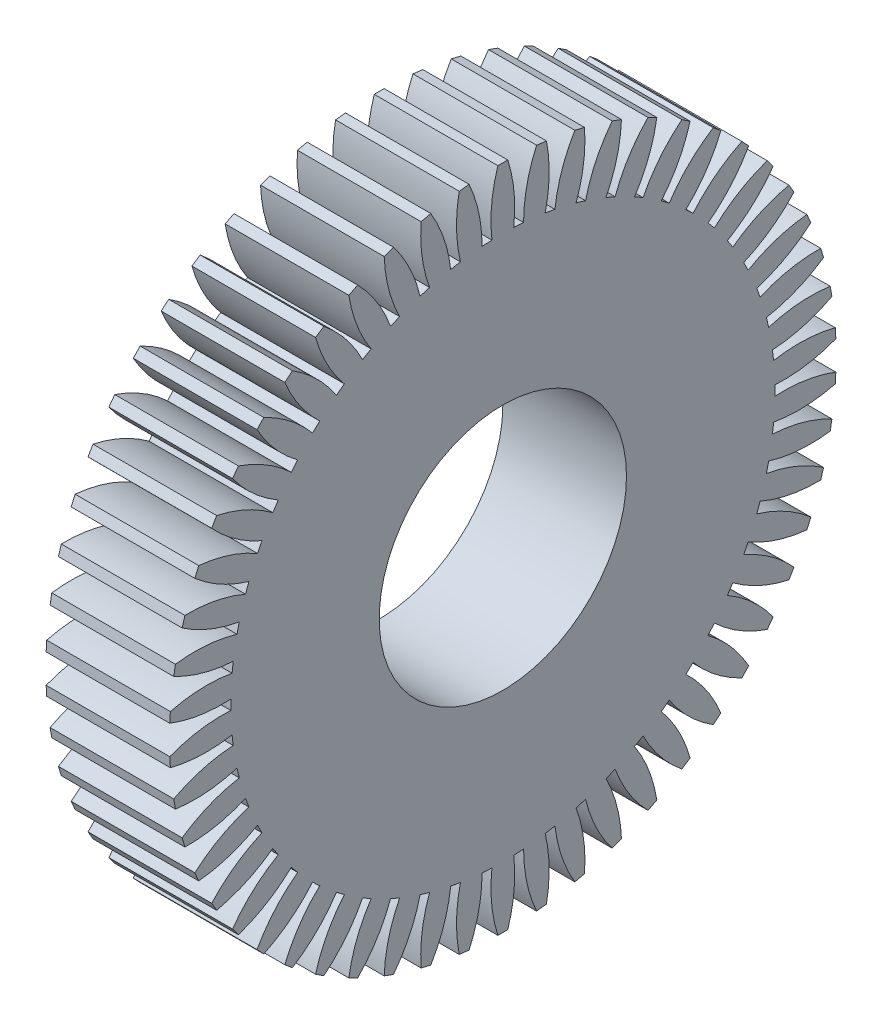
SolidWorks part; units mm, degrees
ref_plane "Front Plane" through (0, 0, 0) normal (1, 0, 0) x (0, 1, 0)
ref_plane "Top Plane" through (0, 0, 0) normal (0, 0, 1) x (0, 1, 0)
ref_plane "Right Plane" through (0, 0, 0) normal (0, 1, 0) x (-1, 0, 0)
sketch "Sketch1" plane through (0, 0, 0) normal (1, 0, 0) x (0, 1, 0)
  circle A0 centre (0, 0) radius 135
  dimension "D1" = 270
extrude "Boss-Extrude1" add sketch "Sketch1" along normal blind 50
sketch "Sketch2" plane through (50, 0, 0) normal (1, 0, 0) x (0, 1, 0)
  line L0 (0, 0) -> (0, 135) construction
  line L1 (0, 0) -> (15.6725, 134.0872) construction
  line L2 (7.8496, 134.7716) -> (12.2573, 210.4497) construction
  line L3 (5.8397, 134.6599) -> (9.8329, 134.4273)
  line L4 (0, 0) -> (7.8363, 134.5436) construction
  line L5 (21.4332, 133.0714) -> (25.3725, 132.3768)
  line L6 (36.737, 129.6834) -> (40.5689, 128.5362)
  line L7 (51.5439, 124.5416) -> (55.2167, 122.9573)
  line L8 (65.6537, 117.7156) -> (69.1179, 115.7156)
  line L9 (78.8758, 109.2977) -> (82.0843, 106.9091)
  line L10 (91.0311, 99.4018) -> (93.9406, 96.6568)
  line L11 (101.9555, 88.1616) -> (104.5266, 85.0974)
  line L12 (111.501, 75.7292) -> (113.699, 72.3872)
  line L13 (119.5387, 62.2726) -> (121.3339, 58.6981)
  line L14 (125.9598, 47.974) -> (127.3279, 44.2152)
  line L15 (130.6776, 33.0266) -> (131.6, 29.1344)
  line L16 (133.6281, 17.6325) -> (134.0925, 13.6596)
  line L17 (134.7716, 2) -> (134.7716, -2)
  line L18 (134.0925, -13.6596) -> (133.6281, -17.6325)
  line L19 (131.6, -29.1344) -> (130.6776, -33.0266)
  line L20 (127.3279, -44.2152) -> (125.9598, -47.974)
  line L21 (121.3339, -58.6981) -> (119.5387, -62.2726)
  line L22 (113.699, -72.3872) -> (111.501, -75.7292)
  line L23 (104.5266, -85.0974) -> (101.9555, -88.1616)
  line L24 (93.9406, -96.6568) -> (91.0311, -99.4018)
  line L25 (82.0843, -106.9091) -> (78.8758, -109.2977)
  line L26 (69.1179, -115.7156) -> (65.6537, -117.7156)
  line L27 (55.2167, -122.9573) -> (51.5439, -124.5416)
  line L28 (40.5689, -128.5362) -> (36.737, -129.6834)
  line L29 (25.3725, -132.3768) -> (21.4332, -133.0714)
  line L30 (9.8329, -134.4273) -> (5.8397, -134.6599)
  line L31 (-5.8397, -134.6599) -> (-9.8329, -134.4273)
  line L32 (-21.4332, -133.0714) -> (-25.3725, -132.3768)
  line L33 (-36.737, -129.6834) -> (-40.5689, -128.5362)
  line L34 (-51.5439, -124.5416) -> (-55.2167, -122.9573)
  line L35 (-65.6537, -117.7156) -> (-69.1179, -115.7156)
  line L36 (-78.8758, -109.2977) -> (-82.0843, -106.9091)
  line L37 (-91.0311, -99.4018) -> (-93.9406, -96.6568)
  line L38 (-101.9555, -88.1616) -> (-104.5266, -85.0974)
  line L39 (-111.501, -75.7292) -> (-113.699, -72.3872)
  line L40 (-119.5387, -62.2726) -> (-121.3339, -58.6981)
  line L41 (-125.9598, -47.974) -> (-127.3279, -44.2152)
  line L42 (-130.6776, -33.0266) -> (-131.6, -29.1344)
  line L43 (-133.6281, -17.6325) -> (-134.0925, -13.6596)
  line L44 (-134.7716, -2) -> (-134.7716, 2)
  line L45 (-134.0925, 13.6596) -> (-133.6281, 17.6325)
  line L46 (-131.6, 29.1344) -> (-130.6776, 33.0266)
  line L47 (-127.3279, 44.2152) -> (-125.9598, 47.974)
  line L48 (-121.3339, 58.6981) -> (-119.5387, 62.2726)
  line L49 (-113.699, 72.3872) -> (-111.501, 75.7292)
  line L50 (-104.5266, 85.0974) -> (-101.9555, 88.1616)
  line L51 (-93.9406, 96.6568) -> (-91.0311, 99.4018)
  line L52 (-82.0843, 106.9091) -> (-78.8758, 109.2977)
  line L53 (-69.1179, 115.7156) -> (-65.6537, 117.7156)
  line L54 (-55.2167, 122.9573) -> (-51.5439, 124.5416)
  line L55 (-40.5689, 128.5362) -> (-36.737, 129.6834)
  line L56 (-25.3725, 132.3768) -> (-21.4332, 133.0714)
  line L57 (-9.8329, 134.4273) -> (-5.8397, 134.6599)
  arc A0 (2, 109.9818) -> (-2, 109.9818) centre (0, 0) ccw
  arc A2 (2, 109.9818) -> (5.8397, 134.6599) centre (60.8496, 113.4632) cw
  arc A5 (10.7816, 109.4703) -> (9.8329, 134.4273) centre (-47.2659, 119.7602) ccw
  arc A6 (23.4175, 107.4785) -> (25.3725, 132.3768) centre (-33.043, 124.4376) ccw
  arc A7 (14.7546, 109.006) -> (21.4332, 133.0714) centre (73.6104, 105.6317) cw
  arc A8 (35.7366, 104.0331) -> (40.5689, 128.5362) centre (-18.3733, 127.4323) ccw
  arc A9 (27.3096, 106.556) -> (36.737, 129.6834) centre (85.3758, 96.3719) cw
  arc A10 (47.5725, 99.1809) -> (55.2167, 122.9573) centre (-3.455, 128.7036) ccw
  arc A11 (39.4954, 102.6651) -> (51.5439, 124.5416) centre (95.9866, 85.8087) cw
  arc A12 (58.765, 92.9875) -> (69.1179, 115.7156) centre (11.5099, 128.2345) ccw
  arc A13 (51.147, 97.3857) -> (65.6537, 117.7156) centre (105.2994, 74.0851) cw
  arc A14 (69.1629, 85.5365) -> (82.0843, 106.9091) centre (26.3192, 126.0312) ccw
  arc A15 (62.107, 90.7894) -> (78.8758, 109.2977) centre (113.1881, 61.3597) cw
  arc A16 (78.6254, 76.9288) -> (93.9406, 96.6568) centre (40.7726, 122.1235) ccw
  arc A17 (72.227, 82.9654) -> (91.0311, 99.4018) centre (119.5462, 47.8044) cw
  arc A18 (87.0246, 67.2808) -> (104.5266, 85.0974) centre (54.6746, 116.5644) ccw
  arc A19 (81.3704, 74.0194) -> (101.9555, 88.1616) centre (124.2876, 33.6027) cw
  arc A20 (94.247, 56.723) -> (113.699, 72.3872) centre (67.8372, 109.4289) ccw
  arc A21 (89.4133, 64.0723) -> (111.501, 75.7292) centre (127.3483, 18.9466) cw
  arc A22 (100.1949, 45.398) -> (121.3339, 58.6981) centre (80.0824, 100.8136) ccw
  arc A23 (96.247, 53.2589) -> (119.5387, 62.2726) centre (128.6868, 4.0343) cw
  arc A24 (104.7878, 33.4591) -> (127.3279, 44.2152) centre (91.2446, 90.8349) ccw
  arc A25 (101.7792, 41.7251) -> (125.9598, 47.974) centre (128.285, -10.9326) cw
  arc A26 (107.9636, 21.0678) -> (131.6, 29.1344) centre (101.173, 79.6278) ccw
  arc A27 (105.935, 29.6272) -> (130.6776, 33.0266) centre (126.1484, -25.7517) cw
  arc A28 (109.6795, 8.3915) -> (134.0925, 13.6596) centre (109.7331, 67.344) ccw
  arc A29 (108.6582, 17.1285) -> (133.6281, 17.6325) centre (122.3058, -40.2225) cw
  arc A30 (109.912, -4.3983) -> (134.7716, -2) centre (116.8093, 54.1494) ccw
  arc A31 (109.912, 4.3983) -> (134.7716, 2) centre (116.8093, -54.1494) cw
  arc A32 (108.6582, -17.1285) -> (133.6281, -17.6325) centre (122.3058, 40.2225) ccw
  arc A33 (109.6795, -8.3915) -> (134.0925, -13.6596) centre (109.7331, -67.344) cw
  arc A34 (105.935, -29.6272) -> (130.6776, -33.0266) centre (126.1484, 25.7517) ccw
  arc A35 (107.9636, -21.0678) -> (131.6, -29.1344) centre (101.173, -79.6278) cw
  arc A36 (101.7792, -41.7251) -> (125.9598, -47.974) centre (128.285, 10.9326) ccw
  arc A37 (104.7878, -33.4591) -> (127.3279, -44.2152) centre (91.2446, -90.8349) cw
  arc A38 (96.247, -53.2589) -> (119.5387, -62.2726) centre (128.6868, -4.0343) ccw
  arc A39 (100.1949, -45.398) -> (121.3339, -58.6981) centre (80.0824, -100.8136) cw
  arc A40 (89.4133, -64.0723) -> (111.501, -75.7292) centre (127.3483, -18.9466) ccw
  arc A41 (94.247, -56.723) -> (113.699, -72.3872) centre (67.8372, -109.4289) cw
  arc A42 (81.3704, -74.0194) -> (101.9555, -88.1616) centre (124.2876, -33.6027) ccw
  arc A43 (87.0246, -67.2808) -> (104.5266, -85.0974) centre (54.6746, -116.5644) cw
  arc A44 (72.227, -82.9654) -> (91.0311, -99.4018) centre (119.5462, -47.8044) ccw
  arc A45 (78.6254, -76.9288) -> (93.9406, -96.6568) centre (40.7726, -122.1235) cw
  arc A46 (62.107, -90.7894) -> (78.8758, -109.2977) centre (113.1881, -61.3597) ccw
  arc A47 (69.1629, -85.5365) -> (82.0843, -106.9091) centre (26.3192, -126.0312) cw
  arc A48 (51.147, -97.3857) -> (65.6537, -117.7156) centre (105.2994, -74.0851) ccw
  arc A49 (58.765, -92.9875) -> (69.1179, -115.7156) centre (11.5099, -128.2345) cw
  arc A50 (39.4954, -102.6651) -> (51.5439, -124.5416) centre (95.9866, -85.8087) ccw
  arc A51 (47.5725, -99.1809) -> (55.2167, -122.9573) centre (-3.455, -128.7036) cw
  arc A52 (27.3096, -106.556) -> (36.737, -129.6834) centre (85.3758, -96.3719) ccw
  arc A53 (35.7366, -104.0331) -> (40.5689, -128.5362) centre (-18.3733, -127.4323) cw
  arc A54 (14.7546, -109.006) -> (21.4332, -133.0714) centre (73.6104, -105.6317) ccw
  arc A55 (23.4175, -107.4785) -> (25.3725, -132.3768) centre (-33.043, -124.4376) cw
  arc A56 (2, -109.9818) -> (5.8397, -134.6599) centre (60.8496, -113.4632) ccw
  arc A57 (10.7816, -109.4703) -> (9.8329, -134.4273) centre (-47.2659, -119.7602) cw
  arc A58 (-10.7816, -109.4703) -> (-9.8329, -134.4273) centre (47.2659, -119.7602) ccw
  arc A59 (-2, -109.9818) -> (-5.8397, -134.6599) centre (-60.8496, -113.4632) cw
  arc A60 (-23.4175, -107.4785) -> (-25.3725, -132.3768) centre (33.043, -124.4376) ccw
  arc A61 (-14.7546, -109.006) -> (-21.4332, -133.0714) centre (-73.6104, -105.6317) cw
  arc A62 (-35.7366, -104.0331) -> (-40.5689, -128.5362) centre (18.3733, -127.4323) ccw
  arc A63 (-27.3096, -106.556) -> (-36.737, -129.6834) centre (-85.3758, -96.3719) cw
  arc A64 (-47.5725, -99.1809) -> (-55.2167, -122.9573) centre (3.455, -128.7036) ccw
  arc A65 (-39.4954, -102.6651) -> (-51.5439, -124.5416) centre (-95.9866, -85.8087) cw
  arc A66 (-58.765, -92.9875) -> (-69.1179, -115.7156) centre (-11.5099, -128.2345) ccw
  arc A67 (-51.147, -97.3857) -> (-65.6537, -117.7156) centre (-105.2994, -74.0851) cw
  arc A68 (-69.1629, -85.5365) -> (-82.0843, -106.9091) centre (-26.3192, -126.0312) ccw
  arc A69 (-62.107, -90.7894) -> (-78.8758, -109.2977) centre (-113.1881, -61.3597) cw
  arc A70 (-78.6254, -76.9288) -> (-93.9406, -96.6568) centre (-40.7726, -122.1235) ccw
  arc A71 (-72.227, -82.9654) -> (-91.0311, -99.4018) centre (-119.5462, -47.8044) cw
  arc A72 (-87.0246, -67.2808) -> (-104.5266, -85.0974) centre (-54.6746, -116.5644) ccw
  arc A73 (-81.3704, -74.0194) -> (-101.9555, -88.1616) centre (-124.2876, -33.6027) cw
  arc A74 (-94.247, -56.723) -> (-113.699, -72.3872) centre (-67.8372, -109.4289) ccw
  arc A75 (-89.4133, -64.0723) -> (-111.501, -75.7292) centre (-127.3483, -18.9466) cw
  arc A76 (-100.1949, -45.398) -> (-121.3339, -58.6981) centre (-80.0824, -100.8136) ccw
  arc A77 (-96.247, -53.2589) -> (-119.5387, -62.2726) centre (-128.6868, -4.0343) cw
  arc A78 (-104.7878, -33.4591) -> (-127.3279, -44.2152) centre (-91.2446, -90.8349) ccw
  arc A79 (-101.7792, -41.7251) -> (-125.9598, -47.974) centre (-128.285, 10.9326) cw
  arc A80 (-107.9636, -21.0678) -> (-131.6, -29.1344) centre (-101.173, -79.6278) ccw
  arc A81 (-105.935, -29.6272) -> (-130.6776, -33.0266) centre (-126.1484, 25.7517) cw
  arc A82 (-109.6795, -8.3915) -> (-134.0925, -13.6596) centre (-109.7331, -67.344) ccw
  arc A83 (-108.6582, -17.1285) -> (-133.6281, -17.6325) centre (-122.3058, 40.2225) cw
  arc A84 (-109.912, 4.3983) -> (-134.7716, 2) centre (-116.8093, -54.1494) ccw
  arc A85 (-109.912, -4.3983) -> (-134.7716, -2) centre (-116.8093, 54.1494) cw
  arc A86 (-108.6582, 17.1285) -> (-133.6281, 17.6325) centre (-122.3058, -40.2225) ccw
  arc A87 (-109.6795, 8.3915) -> (-134.0925, 13.6596) centre (-109.7331, 67.344) cw
  arc A88 (-105.935, 29.6272) -> (-130.6776, 33.0266) centre (-126.1484, -25.7517) ccw
  arc A89 (-107.9636, 21.0678) -> (-131.6, 29.1344) centre (-101.173, 79.6278) cw
  arc A90 (-101.7792, 41.7251) -> (-125.9598, 47.974) centre (-128.285, -10.9326) ccw
  arc A91 (-104.7878, 33.4591) -> (-127.3279, 44.2152) centre (-91.2446, 90.8349) cw
  arc A92 (-96.247, 53.2589) -> (-119.5387, 62.2726) centre (-128.6868, 4.0343) ccw
  arc A93 (-100.1949, 45.398) -> (-121.3339, 58.6981) centre (-80.0824, 100.8136) cw
  arc A94 (-89.4133, 64.0723) -> (-111.501, 75.7292) centre (-127.3483, 18.9466) ccw
  arc A95 (-94.247, 56.723) -> (-113.699, 72.3872) centre (-67.8372, 109.4289) cw
  arc A96 (-81.3704, 74.0194) -> (-101.9555, 88.1616) centre (-124.2876, 33.6027) ccw
  arc A97 (-87.0246, 67.2808) -> (-104.5266, 85.0974) centre (-54.6746, 116.5644) cw
  arc A98 (-72.227, 82.9654) -> (-91.0311, 99.4018) centre (-119.5462, 47.8044) ccw
  arc A99 (-78.6254, 76.9288) -> (-93.9406, 96.6568) centre (-40.7726, 122.1235) cw
  arc A100 (-62.107, 90.7894) -> (-78.8758, 109.2977) centre (-113.1881, 61.3597) ccw
  arc A101 (-69.1629, 85.5365) -> (-82.0843, 106.9091) centre (-26.3192, 126.0312) cw
  arc A102 (-51.147, 97.3857) -> (-65.6537, 117.7156) centre (-105.2994, 74.0851) ccw
  arc A103 (-58.765, 92.9875) -> (-69.1179, 115.7156) centre (-11.5099, 128.2345) cw
  arc A104 (-39.4954, 102.6651) -> (-51.5439, 124.5416) centre (-95.9866, 85.8087) ccw
  arc A105 (-47.5725, 99.1809) -> (-55.2167, 122.9573) centre (3.455, 128.7036) cw
  arc A106 (-27.3096, 106.556) -> (-36.737, 129.6834) centre (-85.3758, 96.3719) ccw
  arc A107 (-35.7366, 104.0331) -> (-40.5689, 128.5362) centre (18.3733, 127.4323) cw
  arc A108 (-14.7546, 109.006) -> (-21.4332, 133.0714) centre (-73.6104, 105.6317) ccw
  arc A109 (-23.4175, 107.4785) -> (-25.3725, 132.3768) centre (33.043, 124.4376) cw
  arc A110 (-2, 109.9818) -> (-5.8397, 134.6599) centre (-60.8496, 113.4632) ccw
  arc A111 (-10.7816, 109.4703) -> (-9.8329, 134.4273) centre (47.2659, 119.7602) cw
  arc A112 (14.7546, 109.006) -> (10.7816, 109.4703) centre (0, 0) ccw
  arc A113 (27.3096, 106.556) -> (23.4175, 107.4785) centre (0, 0) ccw
  arc A114 (39.4954, 102.6651) -> (35.7366, 104.0331) centre (0, 0) ccw
  arc A115 (51.147, 97.3857) -> (47.5725, 99.1809) centre (0, 0) ccw
  arc A116 (62.107, 90.7894) -> (58.765, 92.9875) centre (0, 0) ccw
  arc A117 (72.227, 82.9654) -> (69.1629, 85.5365) centre (0, 0) ccw
  arc A118 (81.3704, 74.0194) -> (78.6254, 76.9288) centre (0, 0) ccw
  arc A119 (89.4133, 64.0723) -> (87.0246, 67.2808) centre (0, 0) ccw
  arc A120 (96.247, 53.2589) -> (94.247, 56.723) centre (0, 0) ccw
  arc A121 (101.7792, 41.7251) -> (100.1949, 45.398) centre (0, 0) ccw
  arc A122 (105.935, 29.6272) -> (104.7878, 33.4591) centre (0, 0) ccw
  arc A123 (108.6582, 17.1285) -> (107.9636, 21.0678) centre (0, 0) ccw
  arc A124 (109.912, 4.3983) -> (109.6795, 8.3915) centre (0, 0) ccw
  arc A125 (109.6795, -8.3915) -> (109.912, -4.3983) centre (0, 0) ccw
  arc A126 (104.7878, -33.4591) -> (105.935, -29.6272) centre (0, 0) ccw
  arc A127 (100.1949, -45.398) -> (101.7792, -41.7251) centre (0, 0) ccw
  arc A128 (94.247, -56.723) -> (96.247, -53.2589) centre (0, 0) ccw
  arc A129 (87.0246, -67.2808) -> (89.4133, -64.0723) centre (0, 0) ccw
  arc A130 (78.6254, -76.9288) -> (81.3704, -74.0194) centre (0, 0) ccw
  arc A131 (107.9636, -21.0678) -> (108.6582, -17.1285) centre (0, 0) ccw
  arc A132 (69.1629, -85.5365) -> (72.227, -82.9654) centre (0, 0) ccw
  arc A133 (58.765, -92.9875) -> (62.107, -90.7894) centre (0, 0) ccw
  arc A134 (47.5725, -99.1809) -> (51.147, -97.3857) centre (0, 0) ccw
  arc A135 (35.7366, -104.0331) -> (39.4954, -102.6651) centre (0, 0) ccw
  arc A136 (23.4175, -107.4785) -> (27.3096, -106.556) centre (0, 0) ccw
  arc A137 (10.7816, -109.4703) -> (14.7546, -109.006) centre (0, 0) ccw
  arc A138 (-2, -109.9818) -> (2, -109.9818) centre (0, 0) ccw
  arc A139 (-14.7546, -109.006) -> (-10.7816, -109.4703) centre (0, 0) ccw
  arc A140 (-27.3096, -106.556) -> (-23.4175, -107.4785) centre (0, 0) ccw
  arc A141 (-39.4954, -102.6651) -> (-35.7366, -104.0331) centre (0, 0) ccw
  arc A142 (-51.147, -97.3857) -> (-47.5725, -99.1809) centre (0, 0) ccw
  arc A143 (-62.107, -90.7894) -> (-58.765, -92.9875) centre (0, 0) ccw
  arc A144 (-72.227, -82.9654) -> (-69.1629, -85.5365) centre (0, 0) ccw
  arc A145 (-81.3704, -74.0194) -> (-78.6254, -76.9288) centre (0, 0) ccw
  arc A146 (-89.4133, -64.0723) -> (-87.0246, -67.2808) centre (0, 0) ccw
  arc A147 (-96.247, -53.2589) -> (-94.247, -56.723) centre (0, 0) ccw
  arc A148 (-101.7792, -41.7251) -> (-100.1949, -45.398) centre (0, 0) ccw
  arc A149 (-105.935, -29.6272) -> (-104.7878, -33.4591) centre (0, 0) ccw
  arc A150 (-108.6582, -17.1285) -> (-107.9636, -21.0678) centre (0, 0) ccw
  arc A151 (-109.912, -4.3983) -> (-109.6795, -8.3915) centre (0, 0) ccw
  arc A152 (-109.6795, 8.3915) -> (-109.912, 4.3983) centre (0, 0) ccw
  arc A153 (-107.9636, 21.0678) -> (-108.6582, 17.1285) centre (0, 0) ccw
  arc A154 (-104.7878, 33.4591) -> (-105.935, 29.6272) centre (0, 0) ccw
  arc A155 (-100.1949, 45.398) -> (-101.7792, 41.7251) centre (0, 0) ccw
  arc A156 (-94.247, 56.723) -> (-96.247, 53.2589) centre (0, 0) ccw
  arc A157 (-87.0246, 67.2808) -> (-89.4133, 64.0723) centre (0, 0) ccw
  arc A158 (-78.6254, 76.9288) -> (-81.3704, 74.0194) centre (0, 0) ccw
  arc A159 (-69.1629, 85.5365) -> (-72.227, 82.9654) centre (0, 0) ccw
  arc A160 (-58.765, 92.9875) -> (-62.107, 90.7894) centre (0, 0) ccw
  arc A161 (-47.5725, 99.1809) -> (-51.147, 97.3857) centre (0, 0) ccw
  arc A162 (-35.7366, 104.0331) -> (-39.4954, 102.6651) centre (0, 0) ccw
  arc A163 (-23.4175, 107.4785) -> (-27.3096, 106.556) centre (0, 0) ccw
  arc A164 (-10.7816, 109.4703) -> (-14.7546, 109.006) centre (0, 0) ccw
  point P333 (0, 0)
  dimension "D1" = 220
  dimension "D2" = 54
  dimension "D3" = 6.667
  dimension "D4" = 3.333
  dimension "D5" = 2
  dimension "D6" = 2
extrude "Cut-Extrude1" cut sketch "Sketch2" against normal through all both and the other way through all flip side to cut
sketch "Sketch3" plane through (50, 0, 0) normal (1, 0, 0) x (0, 1, 0)
  circle A0 centre (0, 0) radius 50
extrude "Cut-Extrude2" cut sketch "Sketch3" against normal through all both and the other way through all
